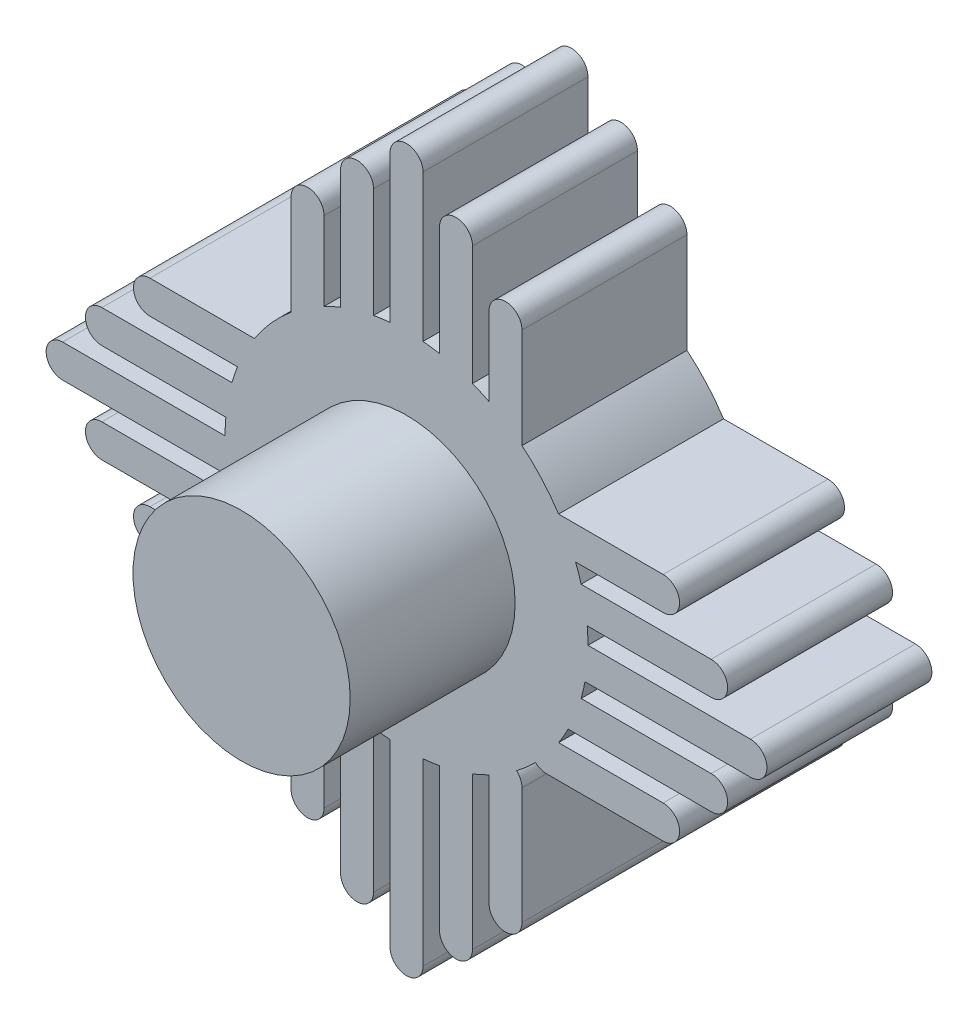
SolidWorks part; units mm, degrees
ref_plane "Front Plane" through (0, 0, 0) normal (0, 0, 1) x (1, 0, 0)
ref_plane "Top Plane" through (0, 0, 0) normal (0, 1, 0) x (1, 0, 0)
ref_plane "Right Plane" through (0, 0, 0) normal (1, 0, 0) x (0, 0, -1)
sketch "Sketch1" plane through (0, 0, 0) normal (0, 0, 1) x (1, 0, 0)
  line L1 (0, 0) -> (50.8, 0)
  line L2 (0, 0) -> (0, 50.8)
  line L3 (0, 50.8) -> (50.8, 50.8)
  line L4 (50.8, 0) -> (50.8, 50.8)
  dimension "D1" = 50.8
  dimension "D2" = 50.8
extrude "Boss-Extrude1" [suppressed] add sketch "Sketch1" along normal blind 3
sketch "Sketch10" [suppressed] plane through (3, 0, 3) normal (0, 0, 1) x (1, 0, 0)
  line L0 (22.4, 0) -> (22.4, 50.8) construction
  line L1 (-3, 0) -> (47.8, 0) construction
  line L2 (47.8, 50.8) -> (-3, 50.8) construction
  line L3 (22.4, 12.7) -> (30.4, 12.7) construction
  line L4 (22.4, 12.7) -> (14.4, 12.7) construction
  line L5 (22.4, 12.7) -> (22.4, 3.2) construction
  line L6 (22.4, 12.7) -> (22.4, 22.2) construction
  line L7 (22.4, 22.2) -> (23.65, 22.2) construction
  line L8 (22.4, 22.2) -> (21.15, 22.2) construction
  line L9 (22.4, 3.2) -> (21.15, 3.2) construction
  line L10 (22.4, 3.2) -> (23.65, 3.2) construction
  line L11 (14.4, 12.7) -> (14.4, 15.425) construction
  line L12 (14.4, 12.7) -> (14.4, 9.975) construction
  line L13 (30.4, 12.7) -> (30.4, 10.475) construction
  line L14 (30.4, 12.7) -> (30.4, 14.925) construction
  line L15 (30.4, 14.925) -> (23.65, 22.2)
  line L16 (23.65, 22.2) -> (21.15, 22.2)
  line L17 (21.15, 22.2) -> (14.4, 15.425)
  line L18 (14.4, 15.425) -> (14.4, 9.975)
  line L19 (14.4, 9.975) -> (21.15, 3.2)
  line L20 (21.15, 3.2) -> (23.65, 3.2)
  line L21 (23.65, 3.2) -> (30.4, 10.475)
  line L22 (30.4, 10.475) -> (30.4, 14.925)
  line L23 (22.4, 50.8) -> (47.8, 25.4) construction
  line L24 (47.8, 0) -> (47.8, 50.8) construction
  line L25 (47.8, 25.4) -> (-3, 25.4) construction
  line L29 (-3, 50.8) -> (-3, 0) construction
  dimension "D1" = 8
  dimension "D2" = 8
  dimension "D3" = 9.5
  dimension "D4" = 9.5
  dimension "D5" = 1.25
  dimension "D6" = 1.25
  dimension "D7" = 1.25
  dimension "D8" = 1.25
  dimension "D9" = 2.725
  dimension "D10" = 2.725
  dimension "D11" = 2.225
  dimension "D12" = 2.225
  dimension "D13" = 3.2
sketch "Sketch8" [suppressed] plane through (3, 0, 3) normal (0, 0, 1) x (1, 0, 0)
  line L0 (22.4, 0) -> (22.4, 3.2) construction
  line L3 (14.4, 9.95) -> (14.4, 16.1175)
  line L4 (6.9625, 17.3875) -> (13.13, 17.3875)
  line L5 (22.4, 12.7) -> (22.4, 3.2) construction
  line L6 (7.2174, 33.6674) -> (13.3849, 33.6674)
  line L7 (14.6549, 34.9374) -> (14.6549, 41.1049)
  line L8 (30.6674, 40.5826) -> (30.6674, 34.4151)
  line L9 (22.4, 3.2) -> (21.15, 3.2) construction
  line L10 (22.4, 3.2) -> (23.65, 3.2) construction
  line L11 (31.9374, 33.1451) -> (38.1049, 33.1451)
  line L12 (37.8249, 17.3749) -> (31.6574, 17.3749)
  line L13 (30.3874, 16.1049) -> (30.3874, 9.9374)
  line L14 (-3, 0) -> (47.8, 0) construction
  line L15 (47.8, 0) -> (47.8, 50.8) construction
  line L16 (22.4, 47.6) -> (23.65, 47.6) construction
  line L17 (22.4, 47.6) -> (21.15, 47.6) construction
  line L18 (47.8, 50.8) -> (-3, 50.8) construction
  line L19 (14.4, 9.95) -> (21.15, 3.2)
  line L20 (21.15, 3.2) -> (23.65, 3.2)
  line L21 (23.65, 3.2) -> (30.3874, 9.9374)
  line L22 (-3, 50.8) -> (-3, 0) construction
  line L23 (22.4, 38.1125) -> (22.4, 47.6) construction
  line L30 (23.65, 47.6) -> (30.6674, 40.5826)
  line L31 (21.15, 47.6) -> (23.65, 47.6)
  line L32 (14.6549, 41.1049) -> (21.15, 47.6)
  line L37 (44.6, 25.4) -> (44.6, 24.15) construction
  line L38 (44.6, 24.15) -> (44.6, 26.65)
  line L40 (44.6, 26.65) -> (38.1049, 33.1451)
  line L44 (37.8249, 17.3749) -> (44.6, 24.15)
  line L45 (44.6, 25.4) -> (44.6, 26.65) construction
  line L50 (0.2, 25.4) -> (0.2, 26.65) construction
  line L54 (0.2, 25.4) -> (0.2, 24.15) construction
  line L58 (6.9625, 17.3875) -> (0.2, 24.15)
  line L59 (0.2, 26.65) -> (7.2174, 33.6674)
  line L60 (0.2, 24.15) -> (0.2, 26.65)
  arc A0 (14.4, 16.1175) -> (13.13, 17.3875) centre (13.13, 16.1175) ccw
  arc A1 (13.3849, 33.6674) -> (14.6549, 34.9374) centre (13.3849, 34.9374) ccw
  arc A2 (30.6674, 34.4151) -> (31.9374, 33.1451) centre (31.9374, 34.4151) ccw
  arc A3 (31.6574, 17.3749) -> (30.3874, 16.1049) centre (31.6574, 16.1049) ccw
  dimension "D5" = 1.27
  dimension "D2" = 3.2
  dimension "D3" = 9.5
  dimension "D4" = 3.2
  dimension "D6" = 3.2
  dimension "D7" = 1.25
  dimension "D8" = 1.25
  dimension "D9" = 3.2
  dimension "D10" = 45
  dimension "D11" = 45
  dimension "D12" = 45
  dimension "D13" = 45
  dimension "D14" = 45
  dimension "D15" = 45
  dimension "D16" = 1.25
  dimension "D17" = 45
  dimension "D18" = 45
extrude "Boss-Extrude2" [suppressed] add sketch "Sketch8" along normal blind 5
fillet "Fillet1" [suppressed] radius 2
sketch "Sketch3" [suppressed] plane through (-3, 0, 3) normal (0, 0, -1) x (-1, 0, 0)
  line L3 (-3, 50.8) -> (-3, 0) construction
  line L7 (-53.8, 50.8) -> (-3, 50.8) construction
  line L8 (-53.8, 0) -> (-53.8, 50.8) construction
  line L9 (-3, 0) -> (-53.8, 0) construction
  circle A0 centre (-15.7, 12.7) radius 3.302
  circle A1 centre (-41.1, 38.1) radius 3.302
  circle A2 centre (-15.7, 38.1) radius 3.302
  circle A3 centre (-41.1, 12.7) radius 3.302
  dimension "D1" = 12.7
  dimension "D3" = 12.7
  dimension "D4" = 12.7
  dimension "D5" = 6.604
  dimension "D2" = 12.7
  dimension "D6" = 12.7
  dimension "D7" = 12.7
  dimension "D8" = 12.7
  dimension "D9" = 12.7
extrude "Cut-Extrude3" [suppressed] cut sketch "Sketch3" along normal through all
fillet "Fillet2" [suppressed] radius 2.54
sketch "Sketch11" plane through (0, 0, 0) normal (0, 0, 1) x (1, 0, 0)
  line L1 (25.4, 31.5071) -> (25.4, 46.2492) construction
  line L2 (24.4, 31.5071) -> (24.4, 46.2492)
  line L3 (26.4, 31.5071) -> (26.4, 46.2492)
  line L4 (28.4, 30.4008) -> (28.4, 43.8677) construction
  line L5 (27.4, 30.4008) -> (27.4, 43.8677)
  line L6 (29.4, 30.4008) -> (29.4, 43.8677)
  line L7 (31.4, 33.8853) -> (31.4, 40.9548) construction
  line L8 (30.4, 33.8853) -> (30.4, 40.9548)
  line L9 (32.4, 33.8853) -> (32.4, 40.9548)
  line L10 (25.4, 38.8782) -> (25.4, 47.6) construction
  line L12 (22.4, 30.4008) -> (22.4, 43.8677) construction
  line L13 (23.4, 30.4008) -> (23.4, 43.8677)
  line L14 (21.4, 30.4008) -> (21.4, 43.8677)
  line L15 (19.4, 33.8853) -> (19.4, 40.9548) construction
  line L16 (20.4, 33.8853) -> (20.4, 40.9548)
  line L17 (18.4, 33.8853) -> (18.4, 40.9548)
  line L18 (38.8782, 25.4) -> (47.6, 25.4) construction
  line L19 (31.5071, 25.4) -> (46.2492, 25.4) construction
  line L20 (31.5071, 26.4) -> (46.2492, 26.4)
  line L21 (31.5071, 24.4) -> (46.2492, 24.4)
  line L22 (30.4008, 22.4) -> (43.8677, 22.4) construction
  line L23 (30.4008, 23.4) -> (43.8677, 23.4)
  line L24 (30.4008, 21.4) -> (43.8677, 21.4)
  line L25 (33.8853, 19.4) -> (40.9548, 19.4) construction
  line L26 (33.8853, 20.4) -> (40.9548, 20.4)
  line L27 (33.8853, 18.4) -> (40.9548, 18.4)
  line L28 (30.4008, 28.4) -> (43.8677, 28.4) construction
  line L29 (30.4008, 27.4) -> (43.8677, 27.4)
  line L30 (30.4008, 29.4) -> (43.8677, 29.4)
  line L31 (33.8853, 31.4) -> (40.9548, 31.4) construction
  line L32 (33.8853, 30.4) -> (40.9548, 30.4)
  line L33 (33.8853, 32.4) -> (40.9548, 32.4)
  line L34 (25.4, 11.9218) -> (25.4, 3.2) construction
  line L35 (25.4, 19.2929) -> (25.4, 4.5508) construction
  line L36 (26.4, 19.2929) -> (26.4, 4.5508)
  line L37 (24.4, 19.2929) -> (24.4, 4.5508)
  line L38 (22.4, 20.3992) -> (22.4, 6.9323) construction
  line L39 (23.4, 20.3992) -> (23.4, 6.9323)
  line L40 (21.4, 20.3992) -> (21.4, 6.9323)
  line L41 (19.4, 16.9147) -> (19.4, 9.8452) construction
  line L42 (20.4, 16.9147) -> (20.4, 9.8452)
  line L43 (18.4, 16.9147) -> (18.4, 9.8452)
  line L44 (28.4, 20.3992) -> (28.4, 6.9323) construction
  line L45 (27.4, 20.3992) -> (27.4, 6.9323)
  line L46 (29.4, 20.3992) -> (29.4, 6.9323)
  line L47 (31.4, 16.9147) -> (31.4, 9.8452) construction
  line L48 (30.4, 16.9147) -> (30.4, 9.8452)
  line L49 (32.4, 16.9147) -> (32.4, 9.8452)
  line L50 (11.9218, 25.4) -> (3.2, 25.4) construction
  line L51 (19.2929, 25.4) -> (4.5508, 25.4) construction
  line L52 (19.2929, 24.4) -> (4.5508, 24.4)
  line L53 (19.2929, 26.4) -> (4.5508, 26.4)
  line L54 (20.3992, 28.4) -> (6.9323, 28.4) construction
  line L55 (20.3992, 27.4) -> (6.9323, 27.4)
  line L56 (20.3992, 29.4) -> (6.9323, 29.4)
  line L57 (16.9147, 31.4) -> (9.8452, 31.4) construction
  line L58 (16.9147, 30.4) -> (9.8452, 30.4)
  line L59 (16.9147, 32.4) -> (9.8452, 32.4)
  line L60 (20.3992, 22.4) -> (6.9323, 22.4) construction
  line L61 (20.3992, 23.4) -> (6.9323, 23.4)
  line L62 (20.3992, 21.4) -> (6.9323, 21.4)
  line L63 (16.9147, 19.4) -> (9.8452, 19.4) construction
  line L64 (16.9147, 20.4) -> (9.8452, 20.4)
  line L65 (16.9147, 18.4) -> (9.8452, 18.4)
  circle A0 centre (25.4, 25.4) radius 11 construction
  arc A1 (24.4, 31.5071) -> (26.4, 31.5071) centre (25.4, 31.5071) ccw
  arc A2 (26.4, 46.2492) -> (24.4, 46.2492) centre (25.4, 46.2492) ccw
  arc A3 (27.4, 30.4008) -> (29.4, 30.4008) centre (28.4, 30.4008) ccw
  arc A4 (29.4, 43.8677) -> (27.4, 43.8677) centre (28.4, 43.8677) ccw
  arc A5 (30.4, 33.8853) -> (32.4, 33.8853) centre (31.4, 33.8853) ccw
  arc A6 (32.4, 40.9548) -> (30.4, 40.9548) centre (31.4, 40.9548) ccw
  arc A7 (23.4, 30.4008) -> (21.4, 30.4008) centre (22.4, 30.4008) cw
  arc A8 (21.4, 43.8677) -> (23.4, 43.8677) centre (22.4, 43.8677) cw
  arc A9 (20.4, 33.8853) -> (18.4, 33.8853) centre (19.4, 33.8853) cw
  arc A10 (18.4, 40.9548) -> (20.4, 40.9548) centre (19.4, 40.9548) cw
  arc A11 (31.5071, 26.4) -> (31.5071, 24.4) centre (31.5071, 25.4) ccw
  arc A12 (46.2492, 24.4) -> (46.2492, 26.4) centre (46.2492, 25.4) ccw
  arc A13 (30.4008, 23.4) -> (30.4008, 21.4) centre (30.4008, 22.4) ccw
  arc A14 (43.8677, 21.4) -> (43.8677, 23.4) centre (43.8677, 22.4) ccw
  arc A15 (33.8853, 20.4) -> (33.8853, 18.4) centre (33.8853, 19.4) ccw
  arc A16 (40.9548, 18.4) -> (40.9548, 20.4) centre (40.9548, 19.4) ccw
  arc A17 (30.4008, 27.4) -> (30.4008, 29.4) centre (30.4008, 28.4) cw
  arc A18 (43.8677, 29.4) -> (43.8677, 27.4) centre (43.8677, 28.4) cw
  arc A19 (33.8853, 30.4) -> (33.8853, 32.4) centre (33.8853, 31.4) cw
  arc A20 (40.9548, 32.4) -> (40.9548, 30.4) centre (40.9548, 31.4) cw
  arc A21 (26.4, 19.2929) -> (24.4, 19.2929) centre (25.4, 19.2929) ccw
  arc A22 (24.4, 4.5508) -> (26.4, 4.5508) centre (25.4, 4.5508) ccw
  arc A23 (23.4, 20.3992) -> (21.4, 20.3992) centre (22.4, 20.3992) ccw
  arc A24 (21.4, 6.9323) -> (23.4, 6.9323) centre (22.4, 6.9323) ccw
  arc A25 (20.4, 16.9147) -> (18.4, 16.9147) centre (19.4, 16.9147) ccw
  arc A26 (18.4, 9.8452) -> (20.4, 9.8452) centre (19.4, 9.8452) ccw
  arc A27 (27.4, 20.3992) -> (29.4, 20.3992) centre (28.4, 20.3992) cw
  arc A28 (29.4, 6.9323) -> (27.4, 6.9323) centre (28.4, 6.9323) cw
  arc A29 (30.4, 16.9147) -> (32.4, 16.9147) centre (31.4, 16.9147) cw
  arc A30 (32.4, 9.8452) -> (30.4, 9.8452) centre (31.4, 9.8452) cw
  arc A31 (19.2929, 24.4) -> (19.2929, 26.4) centre (19.2929, 25.4) ccw
  arc A32 (4.5508, 26.4) -> (4.5508, 24.4) centre (4.5508, 25.4) ccw
  arc A33 (20.3992, 27.4) -> (20.3992, 29.4) centre (20.3992, 28.4) ccw
  arc A34 (6.9323, 29.4) -> (6.9323, 27.4) centre (6.9323, 28.4) ccw
  arc A35 (16.9147, 30.4) -> (16.9147, 32.4) centre (16.9147, 31.4) ccw
  arc A36 (9.8452, 32.4) -> (9.8452, 30.4) centre (9.8452, 31.4) ccw
  arc A37 (20.3992, 23.4) -> (20.3992, 21.4) centre (20.3992, 22.4) cw
  arc A38 (6.9323, 21.4) -> (6.9323, 23.4) centre (6.9323, 22.4) cw
  arc A39 (16.9147, 20.4) -> (16.9147, 18.4) centre (16.9147, 19.4) cw
  arc A40 (9.8452, 18.4) -> (9.8452, 20.4) centre (9.8452, 19.4) cw
  point P6 (25.4, 38.8782)
  point P15 (28.4, 37.1343)
  point P22 (31.4, 37.4201)
  point P31 (22.4, 37.1343)
  point P38 (19.4, 37.4201)
  point P48 (38.8782, 25.4)
  point P57 (37.1343, 22.4)
  point P64 (37.4201, 19.4)
  point P71 (37.1343, 28.4)
  point P78 (37.4201, 31.4)
  point P85 (25.4, 11.9218)
  point P94 (22.4, 13.6657)
  point P101 (19.4, 13.3799)
  point P108 (28.4, 13.6657)
  point P115 (31.4, 13.3799)
  point P122 (11.9218, 25.4)
  point P131 (13.6657, 28.4)
  point P138 (13.3799, 31.4)
  point P145 (13.6657, 22.4)
  point P152 (13.3799, 19.4)
  dimension "D2" = 2
  dimension "D3" = 3
  dimension "D4" = 3
  dimension "D5" = 2
  dimension "D6" = 2
extrude "Boss-Extrude3" add sketch "Sketch11" along normal blind 10
sketch "Sketch12" plane through (0, 0, 0) normal (0, 0, 1) x (1, 0, 0)
  circle A0 centre (25.4, 26.4) radius 11
extrude "Boss-Extrude4" add sketch "Sketch12" along normal blind 10
sketch "Sketch13" plane through (0, 0, 10) normal (0, 0, 1) x (1, 0, 0)
  circle A0 centre (25.4, 26.4) radius 6.585
  dimension "D1" = 13.17
extrude "Boss-Extrude5" add sketch "Sketch13" along normal blind 10
